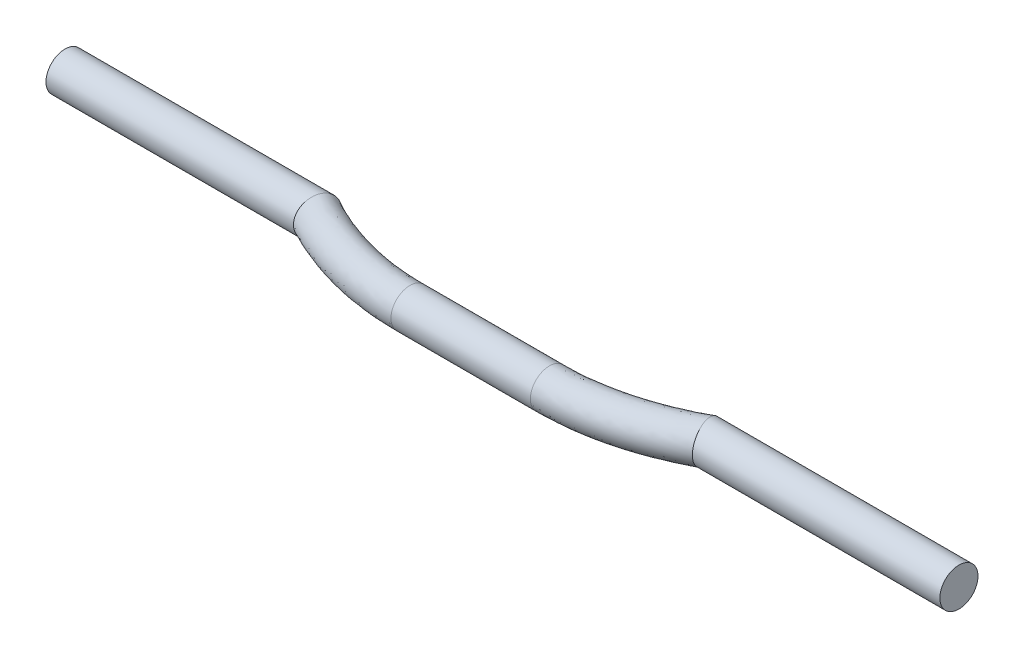
SolidWorks part; units mm, degrees
ref_plane "前视基准面" through (0, 0, 0) normal (0, 0, 1) x (1, 0, 0)
ref_plane "上视基准面" through (0, 0, 0) normal (0, 1, 0) x (1, 0, 0)
ref_plane "右视基准面" through (0, 0, 0) normal (1, 0, 0) x (0, 0, -1)
sketch "Sketch1" plane through (0, 0, 0) normal (0, 1, 0) x (1, 0, 0)
  line L0 (-47, 0) -> (47, 0)
  line L1 (131.3072, 17.0153) -> (301.3072, 17.0153)
  line L2 (0, 17.0153) -> (46.9988, 17.0153)
  line L3 (131.3072, 42.7153) -> (301.3072, 42.7153)
  line L4 (301.3072, 42.7153) -> (301.3072, 17.0153)
  line L5 (301.3072, 29.8653) -> (131.3072, 29.8653)
  line L6 (79.0811, 0) -> (14.9179, 0) construction
  line L7 (81.4759, 17.0153) -> (12.5217, 17.0153) construction
  line L8 (12.1731, 8.1167) -> (81.8269, 8.1167) construction
  line L9 (47, 8.1167) -> (0, 8.1167)
  spline S0 degree 2 poles (47, 0) (87.102, 0) (131.3072, 17.0153) knots 0 0 0 1 1 1
  spline S1 degree 2 poles (46.9988, 17.0153) (90.0951, 17.0153) (131.3072, 42.7153) knots 0 0 0 1 1 1
  spline S2 degree 2 poles (131.3072, 29.8653) (90.5336, 8.1167) (47, 8.1167) knots 0 0 0 1 1 1
  point P3 (0, 0)
  dimension "D1" = 94
  dimension "D2" = 170
  dimension "D3" = 25.7
ref_plane "Plane1" through (301.3072, 0, 0) normal (1, 0, 0) x (0, 0, -1)
sketch "Sketch2" plane through (301.3072, 0, 0) normal (1, 0, 0) x (0, 0, -1)
  line L0 (42.7153, 0) -> (17.0153, 0) construction
  circle A0 centre (29.8653, 0) radius 12.85
  dimension "D1" = 25.7
sweep "Sweep1" add profiles "Sketch2" path "Sketch1"
mirror "Mirror1" about plane through (0, 0, 0) normal (1, 0, 0) of "Sweep1"
